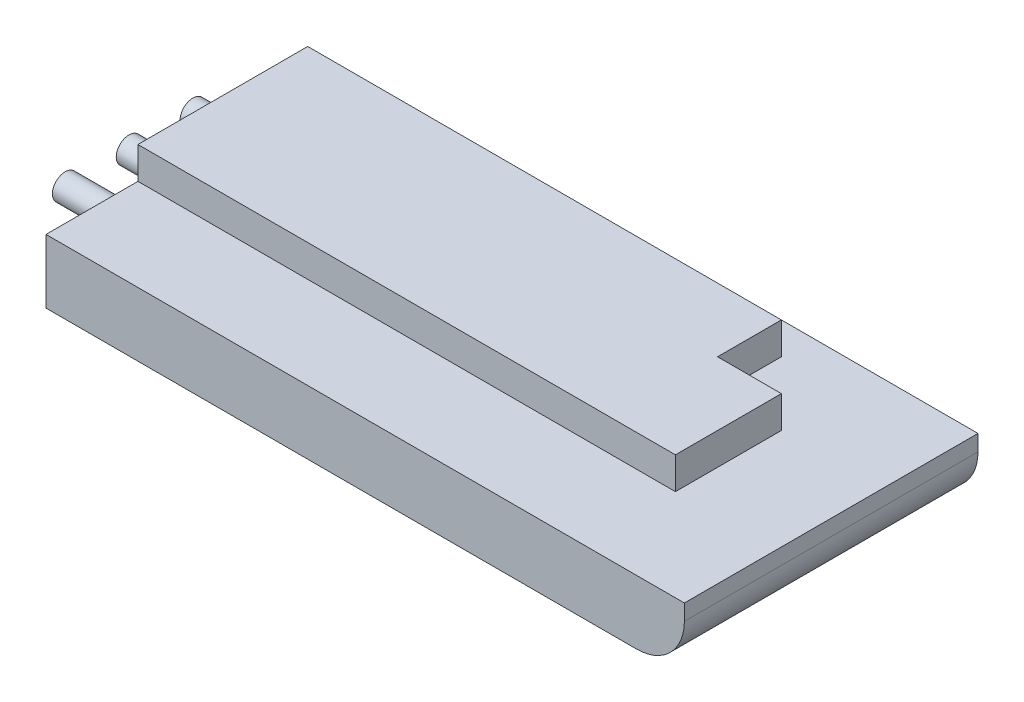
SolidWorks part; units mm, degrees
ref_plane "Front Plane" through (0, 0, 0) normal (0, 0, 1) x (1, 0, 0)
ref_plane "Top Plane" through (0, 0, 0) normal (0, 1, 0) x (1, 0, 0)
ref_plane "Right Plane" through (0, 0, 0) normal (1, 0, 0) x (0, 0, -1)
sketch "Sketch1" plane through (0, 0, 0) normal (0, 1, 0) x (1, 0, 0)
  line L1 (0, 0) -> (254, 0)
  line L2 (0, 0) -> (0, 58.42)
  line L3 (0, 58.42) -> (254, 58.42)
  line L4 (254, 0) -> (254, 58.42)
  dimension "D1" = 254
  dimension "D2" = 58.42
extrude "Boss-Extrude1" add sketch "Sketch1" along normal blind 19.05
sketch "Sketch2" plane through (0, 19.05, 0) normal (0, 1, 0) x (1, 0, 0)
  line L0 (221.234, 18.288) -> (221.234, 52.07)
  line L1 (221.234, 52.07) -> (32.766, 52.07)
  line L2 (221.234, 18.288) -> (32.766, 18.288)
  line L3 (127, 0) -> (127, 58.42) construction
  line L4 (0, 0) -> (254, 0) construction
  line L5 (254, 58.42) -> (0, 58.42) construction
  line L6 (254, 0) -> (254, 58.42) construction
  line L7 (32.766, 18.288) -> (32.766, 52.07)
  point P13 (127, 52.07)
  point P14 (127, 18.288)
  line M5 (0, 58.42) -> (0, 0)
  line M6 (0, 0) -> (254, 0)
  line M7 (254, 0) -> (254, 58.42)
  line M8 (254, 58.42) -> (0, 58.42)
  dimension "D1" = 18.288
  dimension "D2" = 6.35
  dimension "D3" = 32.766
extrude "Cut-Extrude1" cut sketch "Sketch2" against normal blind 6.35 contours L3 L1 L0 L2 M6 M7 M8 | L3 L2 L7 L1 M6 M8 M5
fillet "Fillet1" radius 9.525 2 edges at (254, 0, -29.21) (0, 0, -29.21)
ref_plane "Plane1" through (127, 0, 0) normal (-1, 0, 0) x (0, 0, 1)
sketch "Sketch3" plane through (0, 0, 0) normal (-1, 0, 0) x (0, 0, 1)
  line L1 (0, 0) -> (-65.0635, 0)
  line L2 (0, 0) -> (0, 25.7224)
  line L3 (0, 25.7224) -> (-65.0635, 25.7224)
  line L4 (-65.0635, 0) -> (-65.0635, 25.7224)
extrude "Cut-Extrude2" cut sketch "Sketch3" against normal up to surface (127 mm away)
sketch "Sketch4" plane through (127, 0, 0) normal (-1, 0, 0) x (0, 0, 1)
  line L0 (-58.42, 6.35) -> (0, 6.35) construction
  line L1 (-58.42, 12.7) -> (-58.42, 0) construction
  line L2 (0, 12.7) -> (0, 0) construction
  line L3 (-29.21, 0) -> (-29.21, 19.05) construction
  line L4 (0, 0) -> (-58.42, 0) construction
  line L5 (-18.288, 19.05) -> (-52.07, 19.05) construction
  line L6 (-55.88, 6.35) -> (2.54, 6.35) construction
  circle A0 centre (-16.51, 6.35) radius 2.54
  circle A1 centre (-29.21, 6.35) radius 2.54
  circle A2 centre (-41.91, 6.35) radius 2.54
  dimension "D1" = 5.08
  dimension "D2" = 12.7
  dimension "D3" = 2
  dimension "D4" = 3
extrude "Boss-Extrude2" add sketch "Sketch4" along normal blind 12.7
sketch "Sketch5" plane through (0, 12.7, 0) normal (0, 1, 0) x (1, 0, 0)
  line L0 (221.234, 18.288) -> (233.934, 18.288)
  line L1 (233.934, 18.288) -> (233.934, 39.37)
  line L2 (233.934, 39.37) -> (221.234, 39.37)
  line L3 (221.234, 18.288) -> (221.234, 52.07) construction
  line L4 (221.234, 39.37) -> (221.234, 18.288)
  dimension "D1" = 12.7
  dimension "D2" = 21.082
extrude "Boss-Extrude3" add sketch "Sketch5" along normal up to surface (6.35 mm away) up to face at (174.117, 19.05, -35.179)
